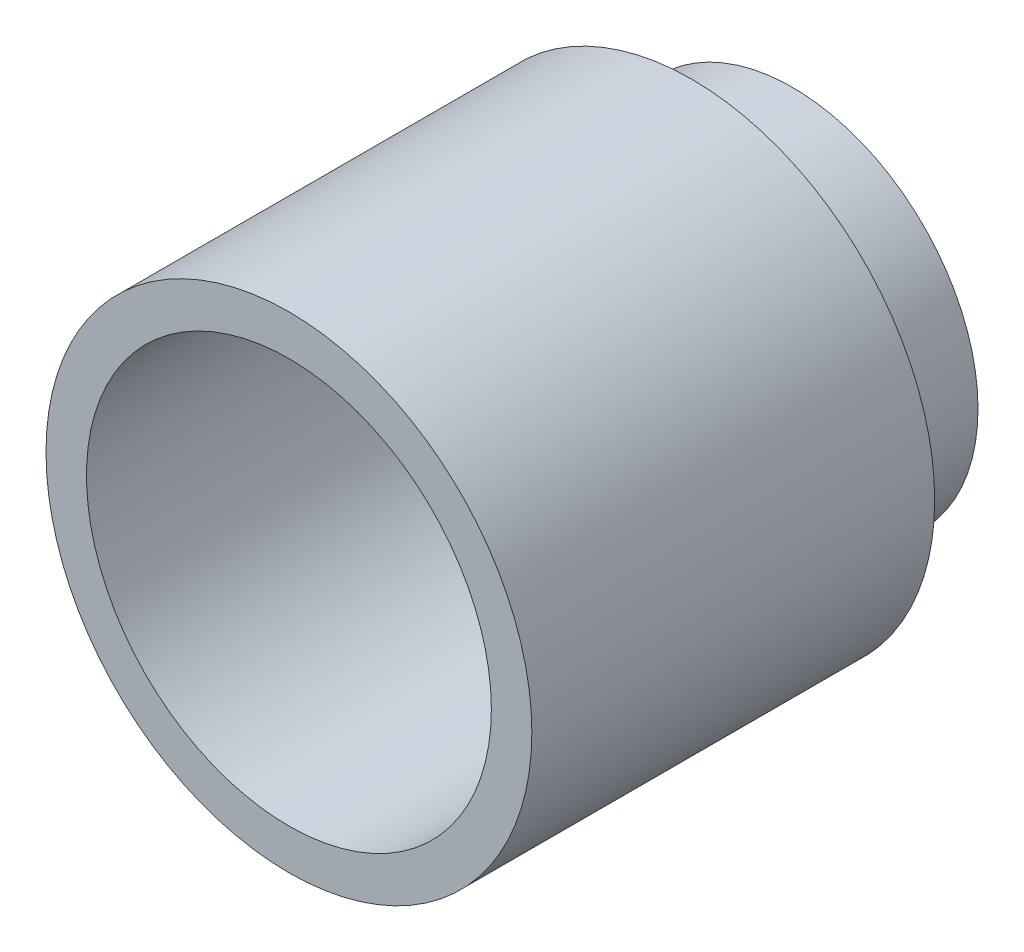
SolidWorks part; units mm, degrees
ref_plane "Front Plane" through (0, 0, 0) normal (0, 0, 1) x (1, 0, 0)
ref_plane "Top Plane" through (0, 0, 0) normal (0, 1, 0) x (1, 0, 0)
ref_plane "Right Plane" through (0, 0, 0) normal (1, 0, 0) x (0, 0, -1)
sketch "Sketch4" plane through (0, 0, 0) normal (0, 0, 1) x (1, 0, 0)
  circle A0 centre (0, 0) radius 15.35
  circle A1 centre (0, 0) radius 18.42
  dimension "D1" = 30.7
  dimension "D2" = 36.84
extrude "Boss-Extrude1" add sketch "Sketch4" along normal blind 20
ref_plane "Plane1" through (0, 0, 10) normal (0, 0, 1) x (1, 0, 0)
sketch "Sketch5" plane through (0, 0, 10) normal (0, 0, 1) x (1, 0, 0)
  circle A0 centre (0, 0) radius 18.42
  circle A1 centre (0, 0) radius 20.1
  dimension "D1" = 40.2
extrude "Boss-Extrude3" add sketch "Sketch5" along normal blind 10 contours A1 | A0
sketch "Sketch6" plane through (0, 0, 10) normal (0, 0, 1) x (1, 0, 0)
  circle A0 centre (0, 0) radius 24.12
  circle A2 centre (0, 0) radius 20.1
  dimension "D1" = 48.24
extrude "Boss-Extrude4" add sketch "Sketch6" along normal blind 40
